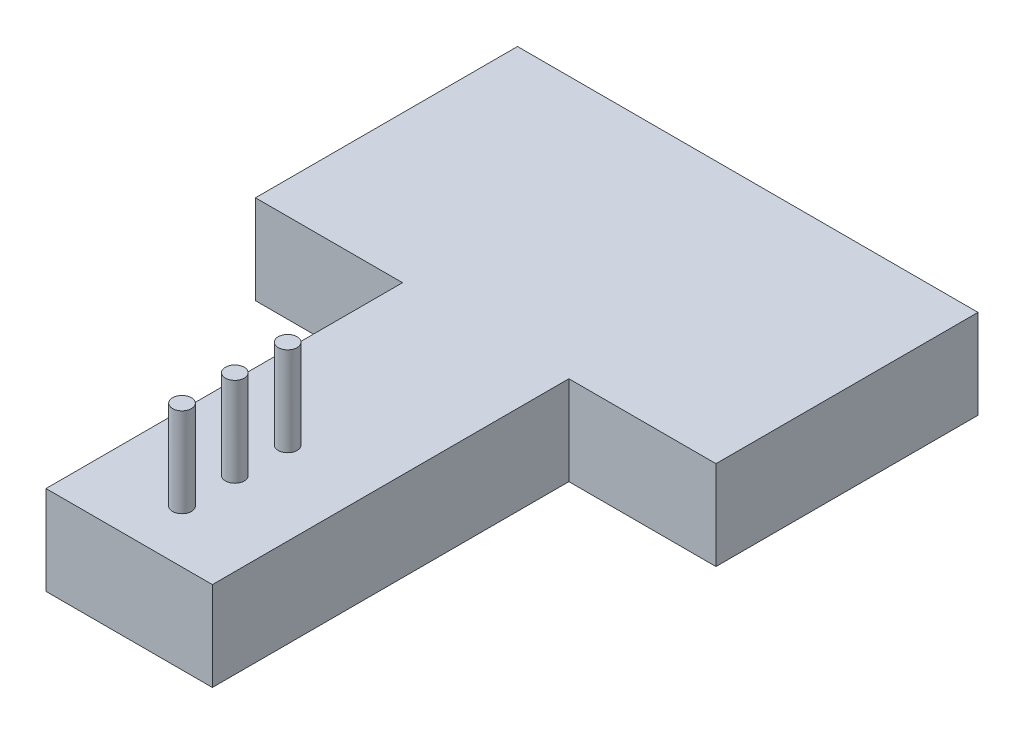
SolidWorks part; units mm, degrees
ref_plane "Front Plane" through (0, 0, 0) normal (0, 0, 1) x (1, 0, 0)
ref_plane "Top Plane" through (0, 0, 0) normal (0, 1, 0) x (1, 0, 0)
ref_plane "Right Plane" through (0, 0, 0) normal (1, 0, 0) x (0, 0, -1)
sketch "Sketch1" plane through (0, 0, 0) normal (0, 1, 0) x (1, 0, 0)
  line L0 (28, 0) -> (77.5, 0)
  line L2 (-28, 0) -> (-28, -120)
  line L3 (-28, -120) -> (28, -120)
  line L4 (28, 0) -> (28, -120)
  line L5 (-77.5, 88.2) -> (77.5, 88.2)
  line L6 (-77.5, 88.2) -> (-77.5, 0)
  line L7 (-77.5, 0) -> (-28, 0)
  line L8 (77.5, 88.2) -> (77.5, 0)
  dimension "D1" = 56
  dimension "D2" = 120
  dimension "D3" = 155
  dimension "D4" = 88.2
extrude "Boss-Extrude1" add sketch "Sketch1" against normal blind 30
sketch "Sketch2" plane through (0, 0, 0) normal (0, 1, 0) x (1, 0, 0)
  line L0 (0, 0) -> (0, -120) construction
  line L1 (-28, -120) -> (28, -120) construction
  circle A0 centre (0, -84.44) radius 3.175
  circle A1 centre (0, -66.66) radius 3.175
  circle A2 centre (0, -102.22) radius 3.175
  point P11 (23.3388, -120)
  point P12 (0, 0)
  point P13 (9.3892, -50.1033)
  dimension "D1" = 6.35
  dimension "D2" = 6.35
  dimension "D3" = 6.35
  dimension "D4" = 17.78
  dimension "D5" = 17.78
  dimension "D6" = 17.78
extrude "Boss-Extrude2" add sketch "Sketch2" along normal blind 30
